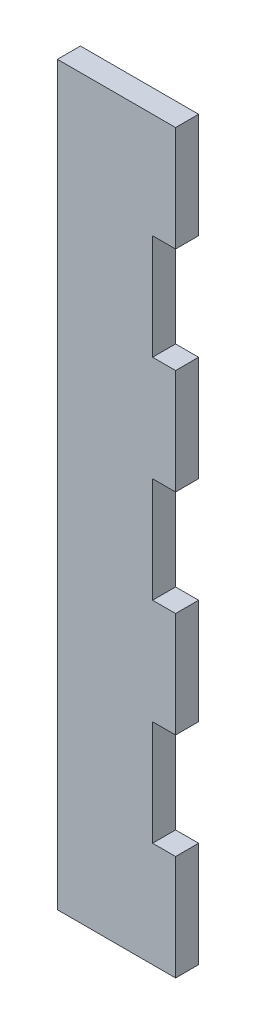
SolidWorks part; units mm, degrees
ref_plane "Front Plane" through (0, 0, 0) normal (0, 0, 1) x (1, 0, 0)
ref_plane "Top Plane" through (0, 0, 0) normal (0, 1, 0) x (1, 0, 0)
ref_plane "Right Plane" through (0, 0, 0) normal (1, 0, 0) x (0, 0, -1)
sketch "Sketch1" plane through (0, 0, 0) normal (0, 0, 1) x (1, 0, 0)
  line L0 (0, 101.6) -> (0, -101.6) construction
  line L1 (-6.35, 101.6) -> (6.35, 101.6)
  line L2 (-6.35, 101.6) -> (-6.35, -101.6)
  line L3 (-6.35, -101.6) -> (6.35, -101.6)
  line L4 (6.35, 101.6) -> (6.35, -101.6)
  line L5 (6.35, 72.5714) -> (6.35, 43.5429)
  line L6 (6.35, 101.6) -> (12.7, 101.6)
  line L7 (6.35, 101.6) -> (6.35, 72.5714)
  line L8 (6.35, 72.5714) -> (12.7, 72.5714)
  line L9 (12.7, 101.6) -> (12.7, 72.5714)
  line L10 (6.35, 72.5714) -> (12.7, 72.5714)
  line L11 (12.7, 72.5714) -> (12.7, 43.5429)
  line L12 (6.35, 43.5429) -> (12.7, 43.5429)
  line L13 (6.35, 43.5429) -> (6.35, 14.5143)
  line L14 (6.35, 43.5429) -> (12.7, 43.5429)
  line L15 (12.7, 43.5429) -> (12.7, 14.5143)
  line L16 (6.35, 14.5143) -> (12.7, 14.5143)
  line L17 (6.35, 14.5143) -> (6.35, -14.5143)
  line L18 (6.35, 14.5143) -> (12.7, 14.5143)
  line L19 (12.7, 14.5143) -> (12.7, -14.5143)
  line L20 (6.35, -14.5143) -> (12.7, -14.5143)
  line L21 (6.35, -14.5143) -> (6.35, -43.5429)
  line L22 (6.35, -14.5143) -> (12.7, -14.5143)
  line L23 (12.7, -14.5143) -> (12.7, -43.5429)
  line L24 (6.35, -43.5429) -> (12.7, -43.5429)
  line L25 (6.35, -43.5429) -> (6.35, -72.5714)
  line L26 (6.35, -43.5429) -> (12.7, -43.5429)
  line L27 (12.7, -43.5429) -> (12.7, -72.5714)
  line L28 (6.35, -72.5714) -> (12.7, -72.5714)
  line L29 (6.35, -72.5714) -> (6.35, -101.6)
  line L30 (6.35, -72.5714) -> (12.7, -72.5714)
  line L31 (12.7, -72.5714) -> (12.7, -101.6)
  line L32 (6.35, -101.6) -> (12.7, -101.6)
  point P6 (0, 0)
  dimension "D2" = 12.7
  dimension "D1" = 203.2
  dimension "D3" = 29.0286
  dimension "D4" = 6.35
  dimension "D5" = 7
extrude "Boss-Extrude1" add sketch "Sketch1" along normal blind 6.35 contours L0 L1 L2 L3 | L1 L0 L3 L4 | L9 L6 L4 L8 | L4 L16 L15 L12 | L4 L24 L23 L20 | L4 L32 L31 L28
sketch "Sketch2" plane through (-6.35, 0, 0) normal (-1, 0, 0) x (0, 0, 1)
  line L1 (0, 101.6) -> (6.35, 101.6)
  line L2 (0, 101.6) -> (0, -101.6)
  line L3 (0, -101.6) -> (6.35, -101.6)
  line L4 (6.35, 101.6) -> (6.35, -101.6)
extrude "Boss-Extrude2" add sketch "Sketch2" along normal blind 13.56
equation "\"Height\"= 12in"
equation "\"Depth\"= 7in"
equation "\"WallThickness\"= 0.25in"
equation "\"FloorThickness\"= 0.25in"
equation "\"Width\" = 30in"
equation "\"D1@Boss-Extrude1\"=\"WallThickness\""
equation "\"D3@Sketch1\"=\"D1@Sketch1\"/\"D5@Sketch1\""
equation "\"D4@Sketch1\"=\"WallThickness\""
